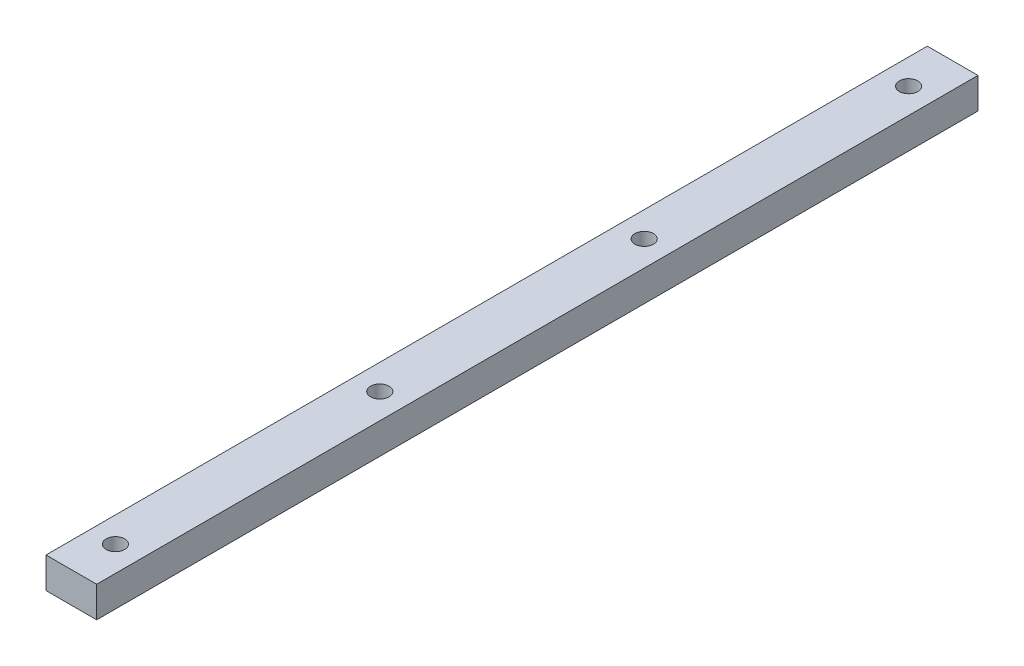
SolidWorks part; units mm, degrees
ref_plane "Front Plane" through (0, 0, 0) normal (0, 0, 1) x (1, 0, 0)
ref_plane "Top Plane" through (0, 0, 0) normal (0, 1, 0) x (1, 0, 0)
ref_plane "Right Plane" through (0, 0, 0) normal (1, 0, 0) x (0, 0, -1)
sketch "Sketch1" plane through (0, 0, 0) normal (0, 0, 1) x (1, 0, 0)
  line L1 (-5.75, -3.5) -> (5.75, -3.5)
  line L2 (-5.75, -3.5) -> (-5.75, 3.5)
  line L3 (-5.75, 3.5) -> (5.75, 3.5)
  line L4 (5.75, -3.5) -> (5.75, 3.5)
  line L5 (-5.75, -3.5) -> (5.75, 3.5) construction
  line L6 (-5.75, 3.5) -> (5.75, -3.5) construction
  point P0 (0, 0)
  dimension "D1" = 11.5
  dimension "D2" = 7
extrude "Boss-Extrude1" add sketch "Sketch1" along normal mid plane 200
hole_wizard "M5 Tapped Hole1" positions "Sketch2" profile "Sketch3" tap size "M5" standard "ISO" end condition through all
sketch "Sketch2" plane through (0, 3.5, 0) normal (0, 1, 0) x (1, 0, 0)
  line L0 (0, 90) -> (0, 30) construction
  line L1 (0, 30) -> (0, -30) construction
  point P0 (0, 90)
  point P14 (0, 30)
  point P15 (0, -30)
  point P16 (0, -90)
  dimension "D2" = 60
  dimension "D1" = 4
sketch "Sketch3" plane through (0, 3.5, -90) normal (1, 0, 0) x (0, 0, 1)
  line L0 (0, 0) -> (0, 7)
  line L1 (0, 7) -> (2.1, 7)
  line L2 (2.1, 7) -> (2.1, 0)
  line L5 (2.1, 0) -> (0, 0)
  line L11 (0, -6.35) -> (0, 107.95) construction
  dimension "Thru Tap Drill Dia." = 4.2
  dimension "Thru Tap Drill Depth" = 7
cosmetic thread "Hole Thread1" parameters "D2"=5
cosmetic thread "Hole Thread2" parameters "D2"=5
cosmetic thread "Hole Thread3" parameters "D2"=5
cosmetic thread "Hole Thread4" parameters "D2"=5
